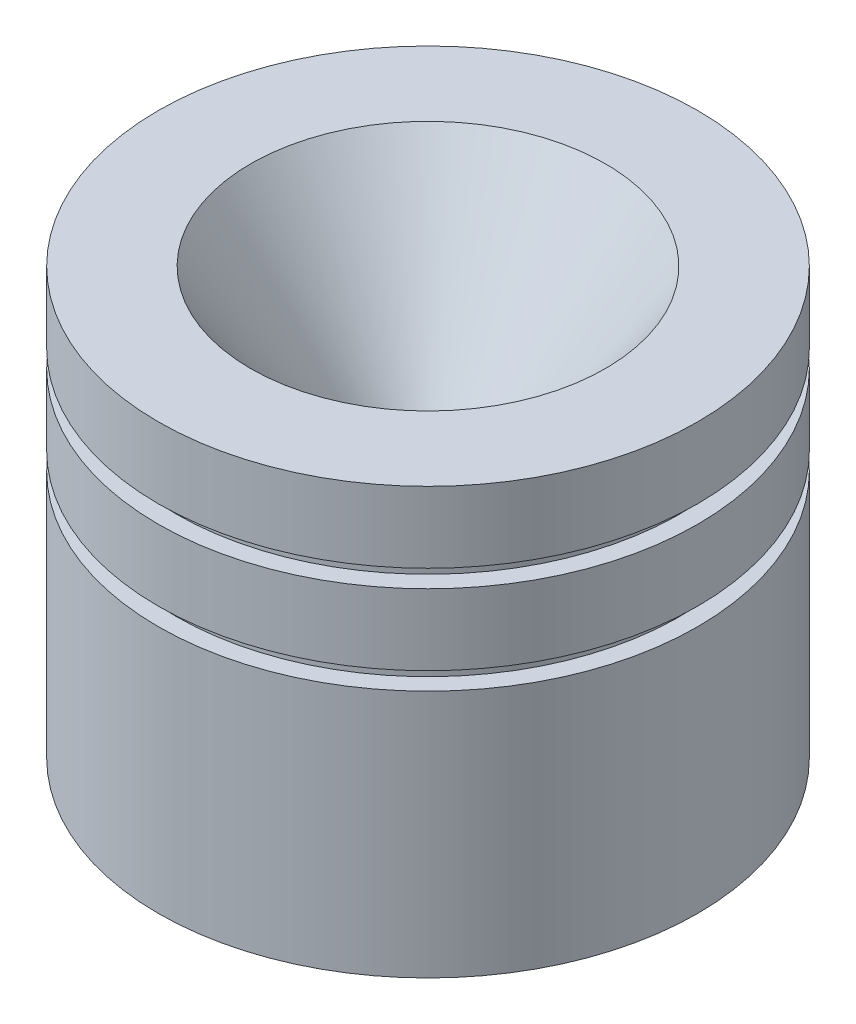
SolidWorks part; units mm, degrees
material "6061 Alloy"
ref_plane "Front Plane" through (0, 0, 0) normal (0, 0, 1) x (1, 0, 0)
ref_plane "Top Plane" through (0, 0, 0) normal (0, 1, 0) x (1, 0, 0)
ref_plane "Right Plane" through (0, 0, 0) normal (1, 0, 0) x (0, 0, -1)
sketch "Sketch2" plane through (0, 0, 0) normal (0, 0, 1) x (1, 0, 0)
  line L0 (48.26, 0) -> (48.26, 76.2)
  line L1 (48.26, 76.2) -> (31.75, 76.2)
  line L2 (31.75, 76.2) -> (6.35, 40.64)
  line L3 (6.35, 40.64) -> (46.99, 0)
  line L4 (46.99, 0) -> (48.26, 0)
  line L5 (0, 0) -> (0, 83.153) construction
  dimension "D1" = 96.52
  dimension "D2" = 12.7
  dimension "D3" = 63.5
  dimension "D4" = 93.98
  dimension "D5" = 45
  dimension "D6" = 76.2
revolve "Revolve1" add sketch "Sketch2" angle 360 about L5
fillet "Fillet1" radius 2.54 1 edges at (0, 40.64, -6.35)
sketch "Sketch3" plane through (0, 0, 0) normal (0, 0, 1) x (1, 0, 0)
  line L0 (48.26, 76.2) -> (-48.26, 76.2) construction
  line L1 (48.26, 76.2) -> (-48.26, 76.2) construction
  line L3 (65.5321, 63.5) -> (45.085, 63.5)
  line L4 (65.5321, 63.5) -> (65.5321, 60.325)
  line L5 (65.5321, 60.325) -> (45.085, 60.325)
  line L6 (45.085, 63.5) -> (45.085, 60.325)
  line L7 (57.785, 47.625) -> (45.085, 47.625)
  line L8 (57.785, 47.625) -> (57.785, 44.45)
  line L9 (57.785, 44.45) -> (45.085, 44.45)
  line L10 (45.085, 47.625) -> (45.085, 44.45)
  dimension "D1" = 3.175
  dimension "D2" = 3.175
  dimension "D3" = 12.7
  dimension "D4" = 12.7
  dimension "D5" = 3.175
  dimension "D6" = 12.7
revolve "Cut-Revolve1" cut sketch "Sketch3" angle 360 about axis through (0, 0, 0) along (0, -1, 0)
